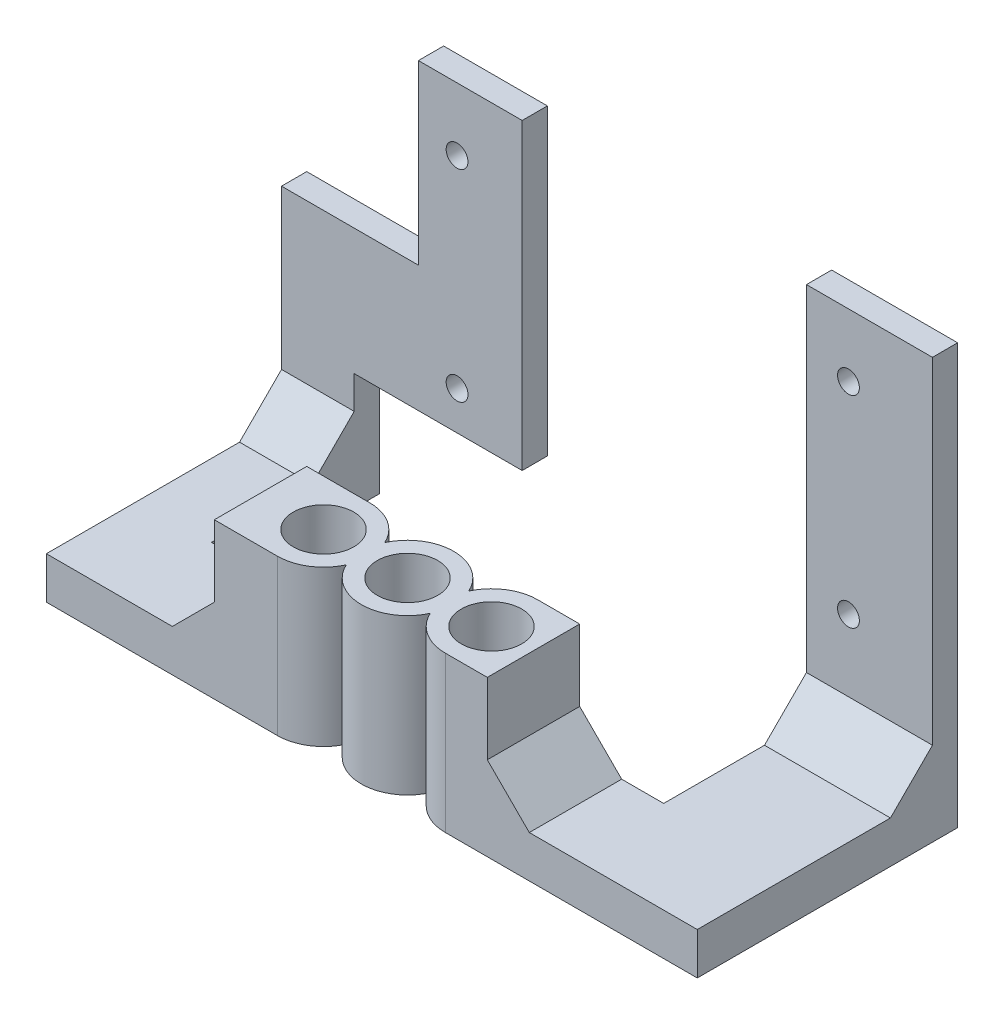
SolidWorks part; units mm, degrees
ref_plane "Front Plane" through (0, 0, 0) normal (0, 0, 1) x (1, 0, 0)
ref_plane "Top Plane" through (0, 0, 0) normal (0, 1, 0) x (1, 0, 0)
ref_plane "Right Plane" through (0, 0, 0) normal (1, 0, 0) x (0, 0, -1)
sketch "Sketch1" plane through (0, 0, 0) normal (0, 0, 1) x (1, 0, 0)
  line L0 (0, 0) -> (0, 35.0275)
  line L5 (0.5, 0) -> (5.5, 0)
  line L6 (5.5, 0) -> (5.5, 18.5)
  line L7 (0.5, 0) -> (0.5, 1)
  line L8 (0.5, 1) -> (1.2, 1)
  line L9 (1.2, 1) -> (1.2, 6)
  line L10 (1.2, 6) -> (3.6, 6)
  line L11 (3.6, 6) -> (3.6, 18.5)
  line L12 (3.6, 18.5) -> (5.5, 18.5)
  dimension "D1" = 0.5
  dimension "D2" = 1.2
  dimension "D3" = 3.6
  dimension "D4" = 5
  dimension "D5" = 5
  dimension "D6" = 1
  dimension "D7" = 17.5
  dimension "D8" = 5.5
revolve "Revolve1" add sketch "Sketch1" angle 360 about L0
ref_plane "Plane1" through (30, 0, 0) normal (1, 0, 0) x (0, 0, -1)
sketch "Sketch3" plane through (30, 0, 0) normal (1, 0, 0) x (0, 0, -1)
  line L0 (-5.5, 18.5) -> (-5.5, 0)
  line L1 (-5.5, 0) -> (5.5, 0)
  line L2 (5.5, 0) -> (5.5, 18.5)
  line L3 (5.5, 18.5) -> (-5.5, 18.5)
extrude "Boss-Extrude1" add sketch "Sketch3" against normal up to surface (30 mm away) up to face at (0, 18.5, -5.5)
sketch "Sketch4" plane through (0, 0, -5.5) normal (0, 0, -1) x (-1, 0, 0)
  line L0 (-15, 50) -> (-15, 0)
  line L2 (0, 0) -> (-30, 0) construction
  line L3 (-15, 0) -> (-30, 0)
  line L4 (-30, 17.05) -> (-30, -17.05) construction
  line L5 (-30, 0) -> (-30, 50)
  line L6 (-30, 50) -> (-15, 50)
  dimension "D1" = 15
  dimension "D2" = 50
extrude "Boss-Extrude2" add sketch "Sketch4" along normal blind 20
sketch "Sketch5" plane through (0, 0, -25.5) normal (0, 0, -1) x (-1, 0, 0)
  line L1 (-15, 0) -> (-15, 50) construction
  line L2 (-30, 0) -> (-15, 0) construction
  circle A0 centre (-20, 42.5) radius 1.3
  circle A1 centre (-20, 18.5) radius 1.3
  dimension "D2" = 42.5
  dimension "D3" = 2.6
  dimension "D4" = 2.6
  dimension "D5" = 5
  dimension "D6" = 5
  dimension "D1" = 24
sketch "Sketch6" plane through (30, 0, 0) normal (1, 0, 0) x (0, 0, -1)
  line L0 (-6.9274, 72.67) -> (-6.9274, 5)
  line L1 (-6.9274, 5) -> (22.5, 5)
  line L2 (22.5, 5) -> (22.5, 72.67)
  line L3 (22.5, 72.67) -> (-6.9274, 72.67)
  line L4 (25.5, 50) -> (25.5, 0) construction
  line L5 (-5.5, 0) -> (25.5, 0) construction
  dimension "D1" = 3
  dimension "D2" = 5
extrude "Cut-Extrude1" cut sketch "Sketch6" against normal blind 25
extrude "Cut-Extrude3" cut sketch "Sketch5" against normal blind 10
ref_plane "Plane2" through (-30, 0, 0) normal (1, 0, 0) x (0, 0, -1)
pattern_linear "LPattern3" count 3 spacing 10 along (-1, 0, 0) of "Revolve1"
ref_plane "Plane3" through (0, 0, -25.5) normal (0, 0, -1) x (-1, 0, 0)
ref_plane "Plane4" through (-27.5, 0, 0) normal (1, 0, 0) x (0, 0, -1)
sketch "Sketch8" plane through (-27.5, 0, 0) normal (1, 0, 0) x (0, 0, -1)
  line L0 (5.5, 0) -> (5.5, 18.5)
  line L1 (5.5, 18.5) -> (-5.5, 18.5)
  line L2 (-5.5, 18.5) -> (-5.5, 0)
  line L3 (-5.5, 0) -> (5.5, 0)
extrude "Boss-Extrude3" add sketch "Sketch8" along normal up to surface (7.5 mm away)
ref_plane "Plane5" through (0, 5, 0) normal (0, 1, 0) x (1, 0, 0)
sketch "Sketch10" plane through (-27.5, 0, 0) normal (-1, 0, 0) x (0, 0, 1)
  line L0 (-5.5, 0) -> (5.5, 0)
  line L1 (5.5, 0) -> (5.5, 5)
  line L2 (13.75, 5) -> (-13.75, 5) construction
  line L3 (5.5, 18.5) -> (5.5, 0) construction
  line L4 (5.5, 5) -> (-5.5, 5)
  line L5 (-5.5, 18.5) -> (-5.5, 0) construction
  line L6 (-5.5, 5) -> (-5.5, 0)
extrude "Boss-Extrude4" add sketch "Sketch10" along normal blind 20
sketch "Sketch11" plane through (0, 0, -5.5) normal (0, 0, -1) x (-1, 0, 0)
  line L0 (47.5, 5) -> (47.5, 0)
  line L1 (47.5, 0) -> (38.8478, 0)
  line L2 (20, 0) -> (47.5, 0) construction
  line L3 (38.8478, 0) -> (38.8478, 5)
  line L4 (47.5, 5) -> (27.5, 5) construction
  line L5 (38.8478, 5) -> (47.5, 5)
extrude "Boss-Extrude5" add sketch "Sketch11" along normal up to surface (20 mm away) up to plane "Plane3"
sketch "Sketch12" plane through (-38.8478, 0, 0) normal (1, 0, 0) x (0, 0, -1)
  line L0 (22.5, 0) -> (22.5, 50)
  line L1 (-5.5, 0) -> (25.5, 0) construction
  line L2 (22.5, 50) -> (25.5, 50)
  line L3 (25.5, -5.5) -> (25.5, 5.5) construction
  line L4 (25.5, 50) -> (25.5, 0)
  line L5 (25.5, 0) -> (22.5, 0)
  line L6 (25.5, 50) -> (22.5, 50) construction
  dimension "D1" = 0
extrude "Boss-Extrude6" add sketch "Sketch12" along normal blind 20 and the other way up to surface (8.6522 mm away) other way up to face at (-47.5, 2.5, -10)
ref_plane "Plane6" through (21.3, 0, 0) normal (-1, 0, 0) x (0, 0, 1)
ref_plane "Plane7" through (-3.3, 0, 0) normal (-1, 0, 0) x (0, 0, 1)
mirror "Mirror1" about plane through (-3.3, 0, 0) normal (-1, 0, 0) of "Cut-Extrude3"
sketch "Sketch14" plane through (0, 0, -22.5) normal (0, 0, 1) x (1, 0, 0)
  line L1 (-18.8478, 0) -> (-38.8478, 0)
  line L2 (-18.8478, 0) -> (-18.8478, 13.9)
  line L3 (-18.8478, 13.9) -> (-38.8478, 13.9)
  line L4 (-38.8478, 0) -> (-38.8478, 13.9)
  line L5 (-47.5, 50) -> (-31.2, 50)
  line L6 (-47.5, 50) -> (-47.5, 28.9)
  line L7 (-47.5, 28.9) -> (-31.2, 28.9)
  line L8 (-31.2, 50) -> (-31.2, 28.9)
  line L9 (-47.5, 50) -> (-18.8478, 50) construction
  circle A0 centre (-26.6, 18.5) radius 1.3 construction
  circle A1 centre (-26.6, 42.5) radius 1.3 construction
  dimension "D1" = 4.6
  dimension "D2" = 15
  dimension "D3" = 4.6
  dimension "D4" = 0
extrude "Cut-Extrude5" cut sketch "Sketch14" against normal blind 10
chamfer "Chamfer2" distance 5 angle 45 4 edges at (5, 5, 0) (22.5, 5, -22.5) (-27.5, 5, 0) (-43.1739, 5, -22.5)
